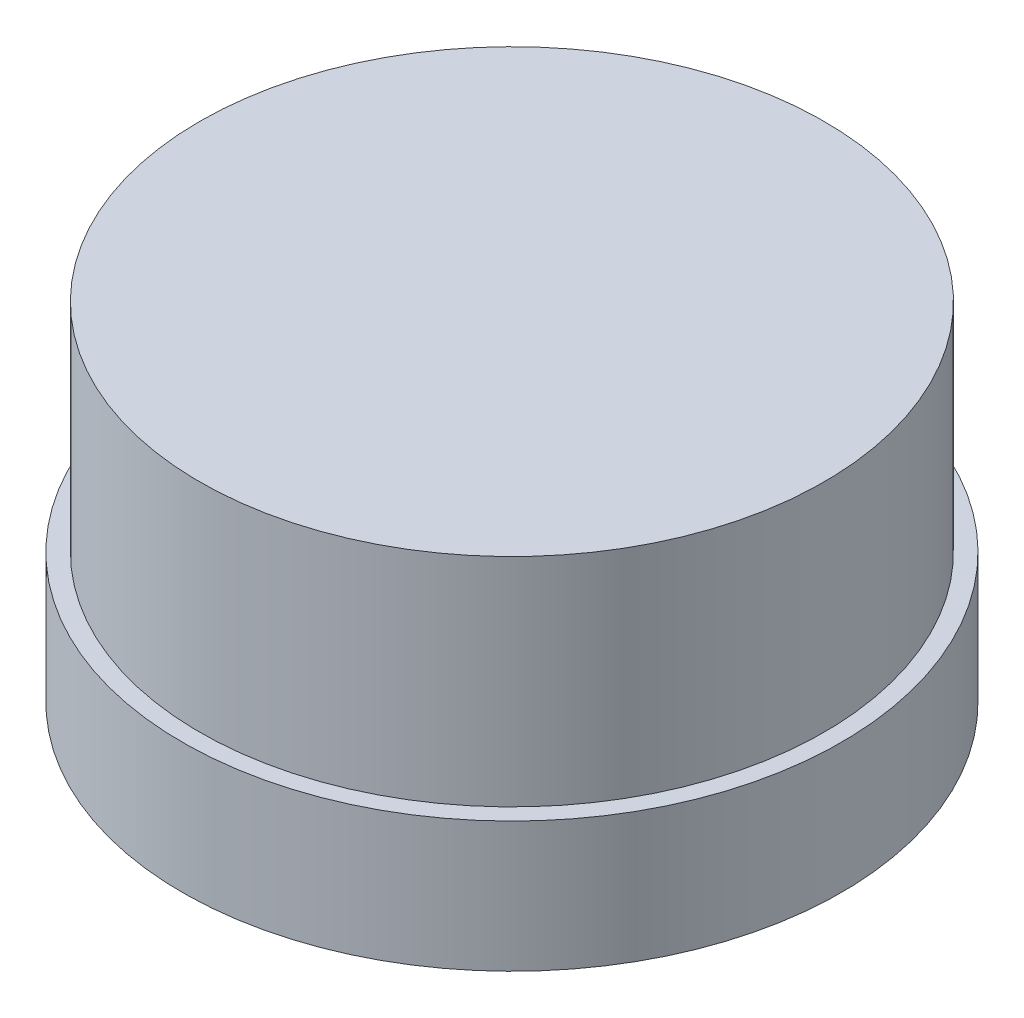
SolidWorks part; units mm, degrees
ref_plane "Front Plane" through (0, 0, 0) normal (0, 0, 1) x (1, 0, 0)
ref_plane "Top Plane" through (0, 0, 0) normal (0, 1, 0) x (1, 0, 0)
ref_plane "Right Plane" through (0, 0, 0) normal (1, 0, 0) x (0, 0, -1)
sketch "Sketch1" plane through (0, 0, 0) normal (0, 0, 1) x (1, 0, 0)
  line L0 (0, 0) -> (38, 0)
  line L1 (38, 0) -> (38, 15)
  line L2 (38, 15) -> (36, 15)
  line L3 (36, 15) -> (36, 40)
  line L4 (36, 40) -> (0, 40)
  line L5 (0, 40) -> (0, 0)
  dimension "D1" = 38
  dimension "D2" = 15
  dimension "D3" = 25
  dimension "D4" = 36
revolve "Revolve1" add sketch "Sketch1" angle 360 about L5
